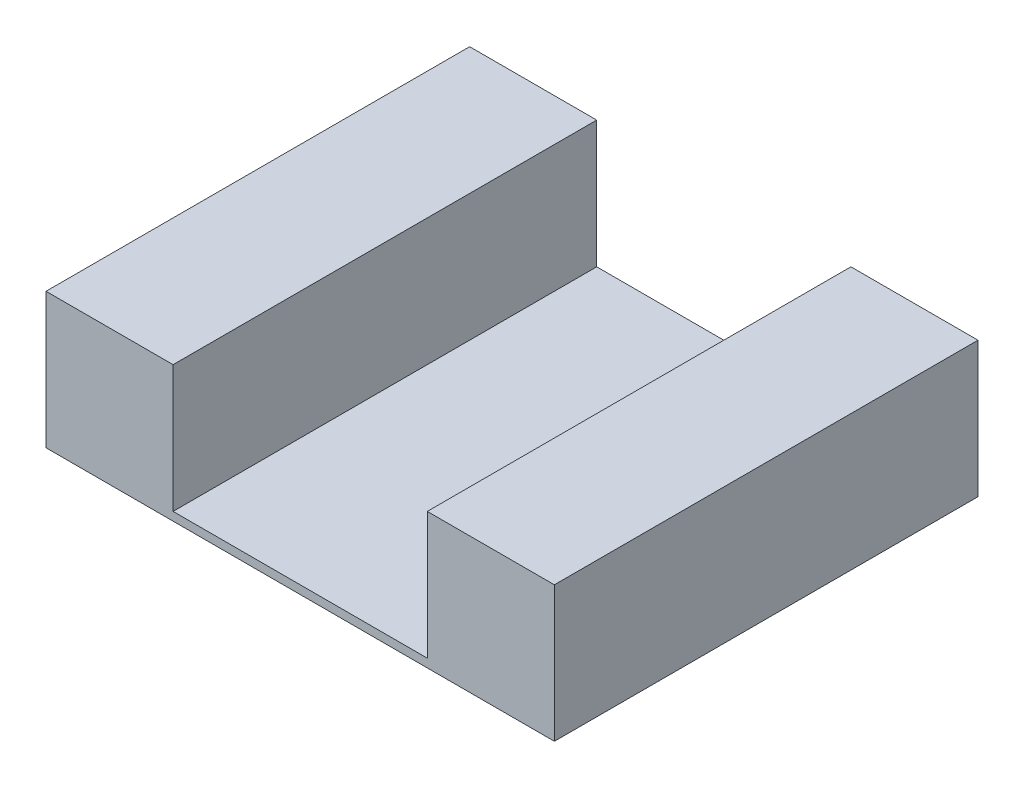
SolidWorks part; units mm, degrees
ref_plane "前视基准面" through (0, 0, 0) normal (0, 0, 1) x (1, 0, 0)
ref_plane "上视基准面" through (0, 0, 0) normal (0, 1, 0) x (1, 0, 0)
ref_plane "右视基准面" through (0, 0, 0) normal (1, 0, 0) x (0, 0, -1)
other "Configuration Table"
sketch "草图1" plane through (0, 0, 0) normal (0, 0, 1) x (1, 0, 0)
  line L0 (0, 0) -> (0, 160)
  line L1 (0, 160) -> (150, 160)
  line L2 (150, 160) -> (150, 10)
  line L3 (150, 10) -> (450, 10)
  line L4 (450, 10) -> (450, 160)
  line L5 (450, 160) -> (600, 160)
  line L6 (600, 160) -> (600, 0)
  line L7 (600, 0) -> (0, 0)
  dimension "D1" = 300
  dimension "D2" = 150
  dimension "D3" = 150
  dimension "D4" = 150
  dimension "D5" = 10
extrude "凸台-拉伸1" add sketch "草图1" along normal blind 500
ref_plane "基准面1" through (300, 0, 0) normal (1, 0, 0) x (0, 0, -1)
